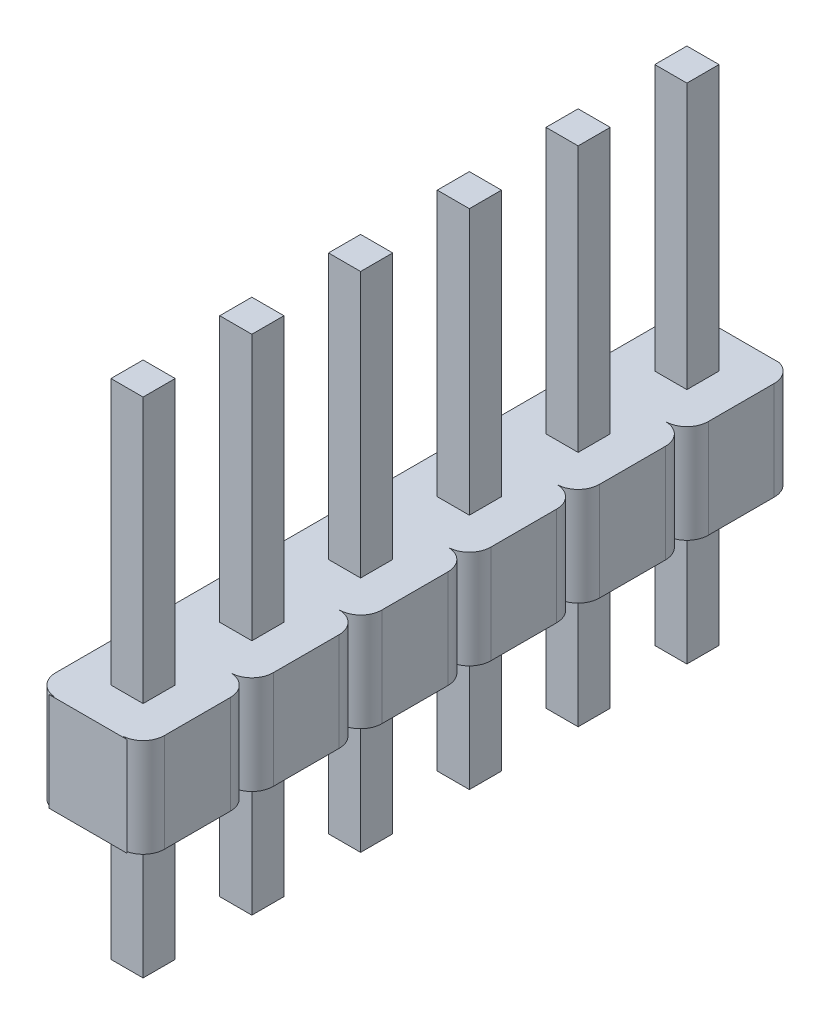
SolidWorks part; units mm, degrees
ref_plane "Alzado" through (0, 0, 0) normal (0, 0, 1) x (1, 0, 0)
ref_plane "Planta" through (0, 0, 0) normal (0, 1, 0) x (1, 0, 0)
ref_plane "Vista lateral" through (0, 0, 0) normal (1, 0, 0) x (0, 0, -1)
ref_plane "Plano1" through (0, 2.3, 0) normal (0, 1, 0) x (1, 0, 0)
sketch "Croquis1" plane through (0, 2.3, 0) normal (0, 1, 0) x (1, 0, 0)
  line L0 (-1.27, -19.07) -> (1.27, -19.07)
  line L1 (1.27, -19.07) -> (1.27, -3.83)
  line L2 (1.27, -3.83) -> (-1.27, -3.83)
  line L3 (-1.27, -3.83) -> (-1.27, -19.07)
extrude "Saliente-Extruir1" add sketch "Croquis1" against normal blind 2.3
sketch "Croquis5" plane through (0, 0, 0) normal (0, -1, 0) x (1, 0, 0)
  line L0 (1.27, 18.55) -> (1.27, 19.55)
  arc A0 (1.27, 19.55) -> (0.77, 19.05) centre (0.77, 19.55) cw
  arc A1 (0.77, 19.05) -> (1.27, 18.55) centre (0.77, 18.55) cw
extrude "Cortar-Extruir4" cut sketch "Croquis5" against normal blind 2.3
sketch "Croquis6" plane through (0, 0, 0) normal (0, -1, 0) x (1, 0, 0)
  line L0 (1.27, 16.01) -> (1.27, 17.01)
  arc A0 (1.27, 17.01) -> (0.77, 16.51) centre (0.77, 17.01) cw
  arc A1 (0.77, 16.51) -> (1.27, 16.01) centre (0.77, 16.01) cw
extrude "Cortar-Extruir5" cut sketch "Croquis6" against normal blind 2.3
sketch "Croquis7" plane through (0, 0, 0) normal (0, -1, 0) x (1, 0, 0)
  line L0 (1.27, 13.47) -> (1.27, 14.47)
  arc A0 (1.27, 14.47) -> (0.77, 13.97) centre (0.77, 14.47) cw
  arc A1 (0.77, 13.97) -> (1.27, 13.47) centre (0.77, 13.47) cw
extrude "Cortar-Extruir6" cut sketch "Croquis7" against normal blind 2.3
sketch "Croquis8" plane through (0, 0, 0) normal (0, -1, 0) x (1, 0, 0)
  line L0 (1.27, 10.93) -> (1.27, 11.93)
  arc A0 (1.27, 11.93) -> (0.77, 11.43) centre (0.77, 11.93) cw
  arc A1 (0.77, 11.43) -> (1.27, 10.93) centre (0.77, 10.93) cw
extrude "Cortar-Extruir7" cut sketch "Croquis8" against normal blind 2.3
sketch "Croquis9" plane through (0, 0, 0) normal (0, -1, 0) x (1, 0, 0)
  line L0 (1.27, 8.39) -> (1.27, 9.39)
  arc A0 (1.27, 9.39) -> (0.77, 8.89) centre (0.77, 9.39) cw
  arc A1 (0.77, 8.89) -> (1.27, 8.39) centre (0.77, 8.39) cw
extrude "Cortar-Extruir8" cut sketch "Croquis9" against normal blind 2.3
sketch "Croquis10" plane through (0, 0, 0) normal (0, -1, 0) x (1, 0, 0)
  line L0 (1.27, 5.85) -> (1.27, 6.85)
  arc A0 (1.27, 6.85) -> (0.77, 6.35) centre (0.77, 6.85) cw
  arc A1 (0.77, 6.35) -> (1.27, 5.85) centre (0.77, 5.85) cw
extrude "Cortar-Extruir9" cut sketch "Croquis10" against normal blind 2.3
sketch "Croquis11" plane through (0, 0, 0) normal (0, -1, 0) x (1, 0, 0)
  line L0 (1.27, 3.31) -> (1.27, 4.31)
  arc A0 (1.27, 4.31) -> (0.77, 3.81) centre (0.77, 4.31) cw
  arc A1 (0.77, 3.81) -> (1.27, 3.31) centre (0.77, 3.31) cw
extrude "Cortar-Extruir10" cut sketch "Croquis11" against normal blind 2.3
sketch "Croquis14" plane through (0, 0, 0) normal (0, -1, 0) x (1, 0, 0)
  line L0 (-1.27, 4.31) -> (-1.27, 3.31)
  arc A0 (-1.27, 3.31) -> (-0.77, 3.81) centre (-0.77, 3.31) cw
  arc A1 (-0.77, 3.81) -> (-1.27, 4.31) centre (-0.77, 4.31) cw
extrude "Cortar-Extruir13" cut sketch "Croquis14" against normal blind 2.3
sketch "Croquis15" plane through (0, 0, 0) normal (0, -1, 0) x (1, 0, 0)
  line L0 (-1.27, 6.85) -> (-1.27, 5.85)
  arc A0 (-1.27, 5.85) -> (-0.77, 6.35) centre (-0.77, 5.85) cw
  arc A1 (-0.77, 6.35) -> (-1.27, 6.85) centre (-0.77, 6.85) cw
extrude "Cortar-Extruir14" cut sketch "Croquis15" against normal blind 2.3
sketch "Croquis16" plane through (0, 0, 0) normal (0, -1, 0) x (1, 0, 0)
  line L0 (-1.27, 9.39) -> (-1.27, 8.39)
  arc A0 (-1.27, 8.39) -> (-0.77, 8.89) centre (-0.77, 8.39) cw
  arc A1 (-0.77, 8.89) -> (-1.27, 9.39) centre (-0.77, 9.39) cw
extrude "Cortar-Extruir15" cut sketch "Croquis16" against normal blind 2.3
sketch "Croquis17" plane through (0, 0, 0) normal (0, -1, 0) x (1, 0, 0)
  line L0 (-1.27, 11.93) -> (-1.27, 10.93)
  arc A0 (-1.27, 10.93) -> (-0.77, 11.43) centre (-0.77, 10.93) cw
  arc A1 (-0.77, 11.43) -> (-1.27, 11.93) centre (-0.77, 11.93) cw
extrude "Cortar-Extruir16" cut sketch "Croquis17" against normal blind 2.3
sketch "Croquis18" plane through (0, 0, 0) normal (0, -1, 0) x (1, 0, 0)
  line L0 (-1.27, 14.47) -> (-1.27, 13.47)
  arc A0 (-1.27, 13.47) -> (-0.77, 13.97) centre (-0.77, 13.47) cw
  arc A1 (-0.77, 13.97) -> (-1.27, 14.47) centre (-0.77, 14.47) cw
extrude "Cortar-Extruir17" cut sketch "Croquis18" against normal blind 2.3
sketch "Croquis19" plane through (0, 0, 0) normal (0, -1, 0) x (1, 0, 0)
  line L0 (-1.27, 17.01) -> (-1.27, 16.01)
  arc A0 (-1.27, 16.01) -> (-0.77, 16.51) centre (-0.77, 16.01) cw
  arc A1 (-0.77, 16.51) -> (-1.27, 17.01) centre (-0.77, 17.01) cw
extrude "Cortar-Extruir18" cut sketch "Croquis19" against normal blind 2.3
sketch "Croquis20" plane through (0, 0, 0) normal (0, -1, 0) x (1, 0, 0)
  line L0 (-1.27, 19.55) -> (-1.27, 18.55)
  arc A0 (-1.27, 18.55) -> (-0.77, 19.05) centre (-0.77, 18.55) cw
  arc A1 (-0.77, 19.05) -> (-1.27, 19.55) centre (-0.77, 19.55) cw
extrude "Cortar-Extruir19" cut sketch "Croquis20" against normal blind 2.3
sketch "Croquis27" plane through (0, 2.3, 0) normal (0, 1, 0) x (-1, 0, 0)
  line L0 (-0.375, 4.705) -> (-0.375, 5.455)
  line L1 (-0.375, 5.455) -> (0.375, 5.455)
  line L2 (0.375, 5.455) -> (0.375, 4.705)
  line L3 (0.375, 4.705) -> (-0.375, 4.705)
extrude "Saliente-Extruir5" add sketch "Croquis27" along normal blind 6.2
sketch "Croquis28" plane through (0, 2.3, 0) normal (0, 1, 0) x (-1, 0, 0)
  line L0 (-0.375, 7.245) -> (-0.375, 7.995)
  line L1 (-0.375, 7.995) -> (0.375, 7.995)
  line L2 (0.375, 7.995) -> (0.375, 7.245)
  line L3 (0.375, 7.245) -> (-0.375, 7.245)
extrude "Saliente-Extruir6" add sketch "Croquis28" along normal blind 6.2
sketch "Croquis29" plane through (0, 2.3, 0) normal (0, 1, 0) x (-1, 0, 0)
  line L0 (-0.375, 9.785) -> (-0.375, 10.535)
  line L1 (-0.375, 10.535) -> (0.375, 10.535)
  line L2 (0.375, 10.535) -> (0.375, 9.785)
  line L3 (0.375, 9.785) -> (-0.375, 9.785)
extrude "Saliente-Extruir7" add sketch "Croquis29" along normal blind 6.2
sketch "Croquis30" plane through (0, 2.3, 0) normal (0, 1, 0) x (-1, 0, 0)
  line L0 (-0.375, 12.325) -> (-0.375, 13.075)
  line L1 (-0.375, 13.075) -> (0.375, 13.075)
  line L2 (0.375, 13.075) -> (0.375, 12.325)
  line L3 (0.375, 12.325) -> (-0.375, 12.325)
extrude "Saliente-Extruir8" add sketch "Croquis30" along normal blind 6.2
sketch "Croquis31" plane through (0, 2.3, 0) normal (0, 1, 0) x (-1, 0, 0)
  line L0 (-0.375, 14.865) -> (-0.375, 15.615)
  line L1 (-0.375, 15.615) -> (0.375, 15.615)
  line L2 (0.375, 15.615) -> (0.375, 14.865)
  line L3 (0.375, 14.865) -> (-0.375, 14.865)
extrude "Saliente-Extruir9" add sketch "Croquis31" along normal blind 6.2
sketch "Croquis32" plane through (0, 2.3, 0) normal (0, 1, 0) x (-1, 0, 0)
  line L0 (-0.375, 17.405) -> (-0.375, 18.155)
  line L1 (-0.375, 18.155) -> (0.375, 18.155)
  line L2 (0.375, 18.155) -> (0.375, 17.405)
  line L3 (0.375, 17.405) -> (-0.375, 17.405)
extrude "Saliente-Extruir10" add sketch "Croquis32" along normal blind 6.2
sketch "Croquis38" plane through (0, 0, 0) normal (0, -1, 0) x (1, 0, 0)
  line L0 (0.375, 5.455) -> (0.375, 4.705)
  line L1 (0.375, 4.705) -> (-0.375, 4.705)
  line L2 (-0.375, 4.705) -> (-0.375, 5.455)
  line L3 (-0.375, 5.455) -> (0.375, 5.455)
extrude "Saliente-Extruir16" add sketch "Croquis38" along normal blind 3.25
sketch "Croquis39" plane through (0, 0, 0) normal (0, -1, 0) x (1, 0, 0)
  line L0 (0.375, 7.995) -> (0.375, 7.245)
  line L1 (0.375, 7.245) -> (-0.375, 7.245)
  line L2 (-0.375, 7.245) -> (-0.375, 7.995)
  line L3 (-0.375, 7.995) -> (0.375, 7.995)
extrude "Saliente-Extruir17" add sketch "Croquis39" along normal blind 3.25
sketch "Croquis40" plane through (0, 0, 0) normal (0, -1, 0) x (1, 0, 0)
  line L0 (0.375, 10.535) -> (0.375, 9.785)
  line L1 (0.375, 9.785) -> (-0.375, 9.785)
  line L2 (-0.375, 9.785) -> (-0.375, 10.535)
  line L3 (-0.375, 10.535) -> (0.375, 10.535)
extrude "Saliente-Extruir18" add sketch "Croquis40" along normal blind 3.25
sketch "Croquis41" plane through (0, 0, 0) normal (0, -1, 0) x (1, 0, 0)
  line L0 (0.375, 13.075) -> (0.375, 12.325)
  line L1 (0.375, 12.325) -> (-0.375, 12.325)
  line L2 (-0.375, 12.325) -> (-0.375, 13.075)
  line L3 (-0.375, 13.075) -> (0.375, 13.075)
extrude "Saliente-Extruir19" add sketch "Croquis41" along normal blind 3.25
sketch "Croquis42" plane through (0, 0, 0) normal (0, -1, 0) x (1, 0, 0)
  line L0 (0.375, 15.615) -> (0.375, 14.865)
  line L1 (0.375, 14.865) -> (-0.375, 14.865)
  line L2 (-0.375, 14.865) -> (-0.375, 15.615)
  line L3 (-0.375, 15.615) -> (0.375, 15.615)
extrude "Saliente-Extruir20" add sketch "Croquis42" along normal blind 3.25
sketch "Croquis43" plane through (0, 0, 0) normal (0, -1, 0) x (1, 0, 0)
  line L0 (0.375, 18.155) -> (0.375, 17.405)
  line L1 (0.375, 17.405) -> (-0.375, 17.405)
  line L2 (-0.375, 17.405) -> (-0.375, 18.155)
  line L3 (-0.375, 18.155) -> (0.375, 18.155)
extrude "Saliente-Extruir21" add sketch "Croquis43" along normal blind 3.25
